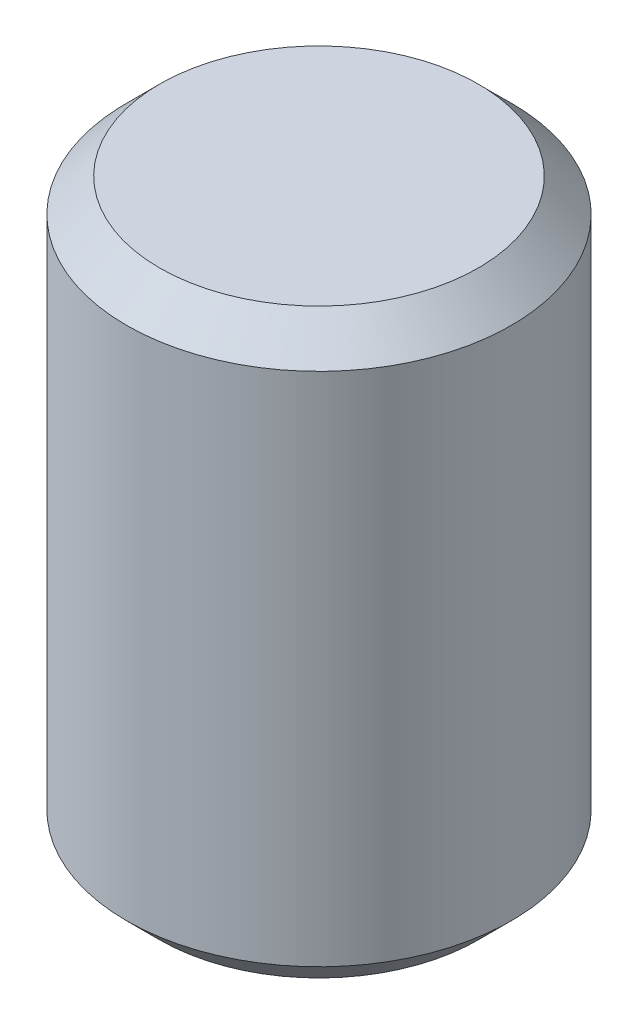
SolidWorks part; units mm, degrees
material "Brass"
ref_plane "Front" through (0, 0, 0) normal (0, 0, 1) x (1, 0, 0)
ref_plane "Top" through (0, 0, 0) normal (0, 1, 0) x (1, 0, 0)
ref_plane "Right" through (0, 0, 0) normal (1, 0, 0) x (0, 0, -1)
sketch "Sketch2" plane through (0, 0, 0) normal (0, 1, 0) x (1, 0, 0)
  circle A0 centre (0, 0) radius 1.1811
  dimension "D1" = 2.3622
extrude "Boss-Extrude1" add sketch "Sketch2" along normal blind 3.5712 contours A0
fillet "Fillet1" radius 0.2032 2 edges at (0, 0, 1.1811) (0, 3.5712, 1.1811) profile chamfer
